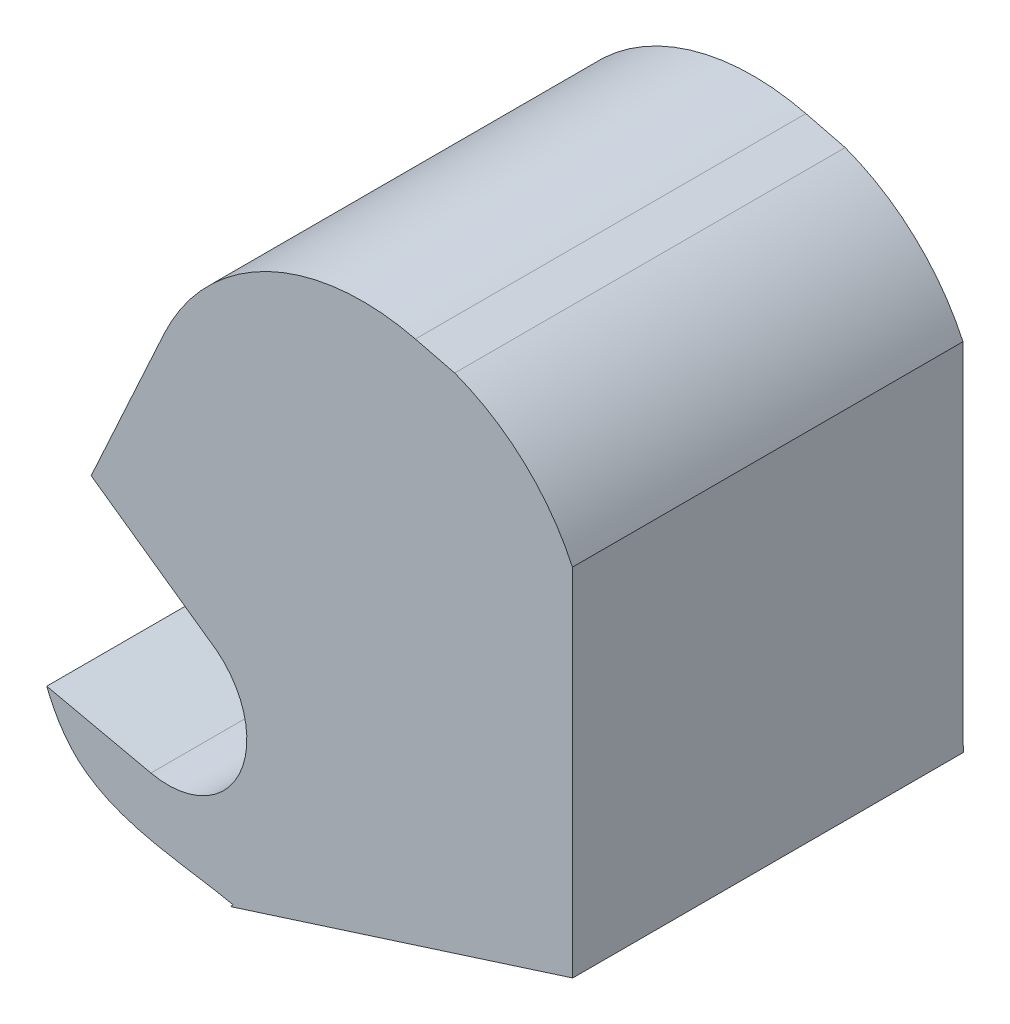
SolidWorks part; units mm, degrees
ref_plane "Front Plane" through (0, 0, 0) normal (0, 0, 1) x (1, 0, 0)
ref_plane "Top Plane" through (0, 0, 0) normal (0, 1, 0) x (1, 0, 0)
ref_plane "Right Plane" through (0, 0, 0) normal (1, 0, 0) x (0, 0, -1)
sketch "Sketch1" plane through (0, 0, 0) normal (0, 0, 1) x (1, 0, 0)
  line L0 (169.5623, -46.1603) -> (169.5526, -34.3208)
  line L1 (169.5623, -46.1603) -> (158.1722, -49.7969)
  line L2 (158.2543, -49.703) -> (158.1722, -49.7969)
  line L3 (165.6318, -30.6839) -> (164.3247, -30.3592)
  line L4 (153.5314, -39.6952) -> (155.9596, -34.3899)
  line L6 (153.5314, -39.6952) -> (157.7166, -42.6498)
  line L7 (155.5205, -47.2722) -> (152.0528, -46.5025)
  arc A0 (164.3247, -30.3592) -> (155.9596, -34.3899) centre (162.5714, -37.4161) ccw
  arc A1 (169.5526, -34.3208) -> (165.6318, -30.6839) centre (163.1637, -37.2766) ccw
  arc A3 (157.7166, -42.6498) -> (155.5205, -47.2722) centre (156.0893, -44.7096) cw
  spline S1 degree 3 poles (158.2543, -49.703) (156.6139, -49.3342) (153.5198, -49.2919) (152.2617, -47.0331) (152.0528, -46.5025) knots 0 0 0 0 0.763192 1 1 1 1
extrude "Boss-Extrude1" add sketch "Sketch1" along normal blind 13 contours A3 L7 S1 L2 L1 L0 A1 L3 A0 L4 L6
